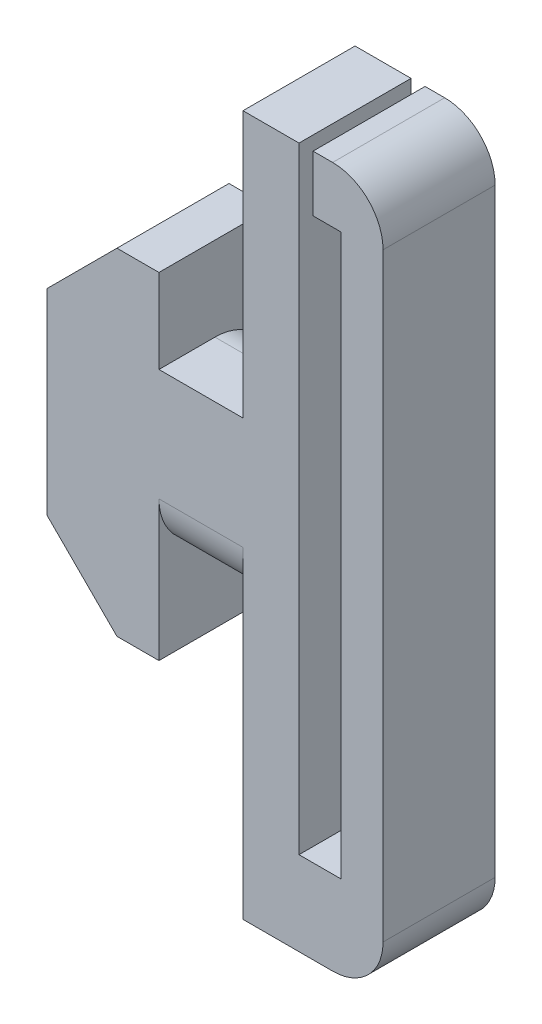
SolidWorks part; units mm, degrees
ref_plane "Płaszczyzna przednia" through (0, 0, 0) normal (0, 0, 1) x (1, 0, 0)
ref_plane "Płaszczyzna górna" through (0, 0, 0) normal (0, 1, 0) x (1, 0, 0)
ref_plane "Płaszczyzna prawa" through (0, 0, 0) normal (1, 0, 0) x (0, 0, -1)
sketch "Szkic1" plane through (0, 0, 0) normal (0, 0, 1) x (1, 0, 0)
  line L0 (0, 0) -> (0, 25)
  line L5 (0, 25) -> (2, 25)
  line L6 (2, 25) -> (2, 3)
  line L7 (2, 3) -> (3.5, 3)
  line L8 (3.5, 3) -> (3.5, 23)
  line L9 (3.5, 23) -> (2.5, 23)
  line L10 (2.5, 23) -> (2.5, 25)
  line L11 (2.5, 25) -> (5, 25)
  line L12 (5, 25) -> (5, 0)
  line L13 (5, 0) -> (0, 0)
  point P2 (0, 0)
  point P13 (0, 0)
  point P14 (0, 0)
  point P15 (0, 0)
  point P16 (0, 0)
  point P17 (0, 0)
  point P18 (0, 0)
  point P19 (4.5906, 21.3808)
  point P20 (5.8507, 0)
  point P21 (3.9801, 21.2078)
  point P22 (4.6996, 25.2367)
  point P23 (3.7354, 21.3808)
  point P24 (0, 0)
  point P25 (0, 0)
  point P26 (3.7171, 25)
  point P27 (0, 0)
  point P28 (0, 0)
  point P29 (0, 0)
  point P30 (0, 0)
  point P31 (0, 0)
  point P32 (0, 0)
  point P33 (0, 0)
  point P34 (0, 0)
  point P35 (0, 0)
  point P36 (0, 0)
  point P37 (0, 0)
  point P38 (0, 0)
  point P39 (0, 0)
  point P40 (0, 0)
  point P41 (0, 0)
  point P42 (0, 0)
  point P43 (0, 0)
  point P44 (0, 0)
  point P45 (0, 0)
extrude "Dodanie-wyciągnięcie1" add sketch "Szkic1" along normal blind 4
fillet "Zaokrąglenie1" radius 1.8 2 edges at (5, 25, 2) (5, 0, 2)
sketch "Szkic2" plane through (0, 0, 0) normal (-1, 0, 0) x (0, 0, 1)
  line L0 (0, 25) -> (0, 0) construction
  line L1 (0, 9.5) -> (4, 9.5)
  line L2 (0, 9.5) -> (0, 15.5)
  line L3 (0, 15.5) -> (4, 15.5)
  line L4 (4, 9.5) -> (4, 15.5)
  line L5 (4, 25) -> (4, 0) construction
  point P8 (0, 0)
  point P9 (0, 0)
extrude "Dodanie-wyciągnięcie2" add sketch "Szkic2" along normal blind 3 contours L1 L4 L3 L2
fillet "Zaokrąglenie2" radius 2 2 edges at (-1.5, 9.5, 4) (-1.5, 15.5, 0)
sketch "Szkic3" plane through (-3, 0, 0) normal (-1, 0, 0) x (0, 0, 1)
  line L1 (0, 6.5) -> (4, 6.5)
  line L2 (0, 6.5) -> (0, 18.5)
  line L3 (0, 18.5) -> (4, 18.5)
  line L4 (4, 6.5) -> (4, 18.5)
  point P4 (0, 0)
  point P6 (0, 0)
extrude "Dodanie-wyciągnięcie3" add sketch "Szkic3" along normal blind 4
chamfer "Sfazowanie1" distance 2.5 angle 45 2 edges at (-7, 6.5, 2) (-7, 18.5, 2)
